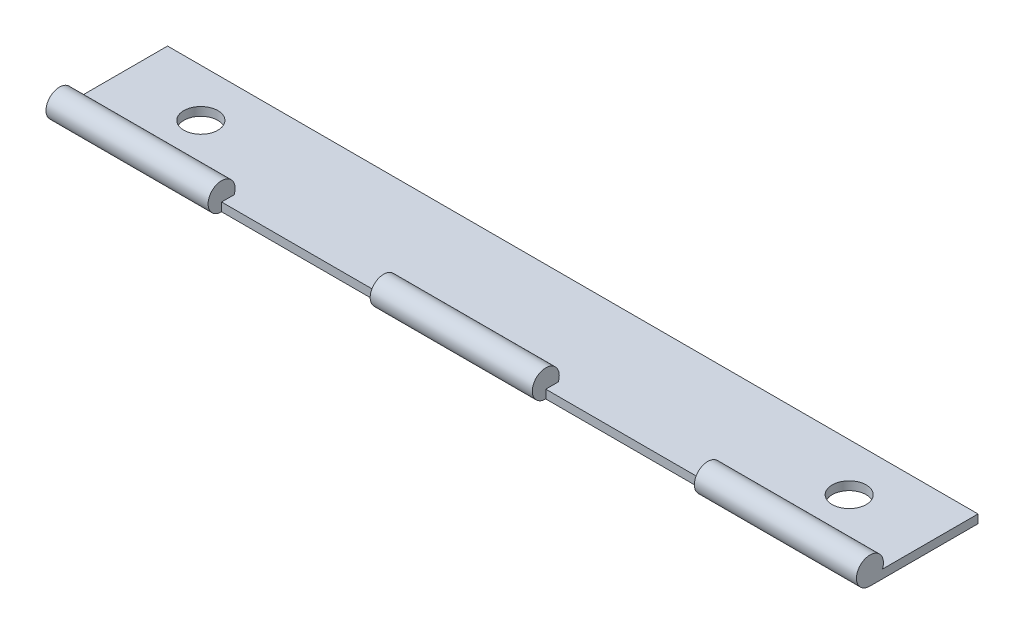
SolidWorks part; units mm, degrees
ref_plane "Front Plane" through (0, 0, 0) normal (0, 0, 1) x (1, 0, 0)
ref_plane "Top Plane" through (0, 0, 0) normal (0, 1, 0) x (1, 0, 0)
ref_plane "Right Plane" through (0, 0, 0) normal (1, 0, 0) x (0, 0, -1)
sketch "Sketch1" plane through (0, 0, 0) normal (0, 1, 0) x (1, 0, 0)
  line L0 (19.05, 12.7) -> (19.05, 0) construction
  line L1 (0, 0) -> (38.1, 0)
  line L2 (0, 0) -> (0, 12.7)
  line L3 (0, 12.7) -> (38.1, 12.7)
  line L4 (38.1, 0) -> (38.1, 12.7)
  dimension "D1" = 12.7
  dimension "D2" = 38.1
extrude "Boss-Extrude1" add sketch "Sketch1" along normal blind 1
sketch "Sketch2" plane through (0, 0, 0) normal (-1, 0, 0) x (0, 0, 1)
  line L0 (0, 0) -> (0, 1.5875) construction
  line L1 (0, 1) -> (0, 0) construction
  circle A0 centre (0, 1.5875) radius 1.5875
  dimension "D1" = 1.5875
extrude "Boss-Extrude2" add sketch "Sketch2" against normal blind 19.05
pattern_linear "MatrizL1" count 2 spacing 38.1 along (1, 0, 0) of "Boss-Extrude1", "Boss-Extrude2"
sketch "Croquis1" plane through (76.2, 0, 0) normal (1, 0, 0) x (0, 0, -1)
  line L1 (12.7, 0) -> (0, 0)
  line L2 (12.7, 0) -> (12.7, 1)
  line L3 (12.7, 1) -> (1.4748, 1)
  line L5 (12.7, 0) -> (0, 1) construction
  line L6 (12.7, 1) -> (0, 0) construction
  arc A0 (1.4748, 1) -> (0, 0) centre (0, 1.5875) ccw
  point P4 (6.35, 0.5)
extrude "Saliente-Extruir1" add sketch "Croquis1" along normal blind 19.05
sketch "Croquis2" plane through (0, 1, 0) normal (0, 1, 0) x (1, 0, 0)
  line L0 (47.625, 1.4748) -> (47.625, 12.7) construction
  line L1 (38.1, 1.4748) -> (57.15, 1.4748) construction
  line L2 (95.25, 12.7) -> (0, 12.7) construction
  line L3 (95.25, 12.7) -> (95.25, 1.4748) construction
  circle A0 centre (85.725, 7.0874) radius 2
  circle A1 centre (9.525, 7.0874) radius 2
  point P12 (95.25, 7.0874)
  dimension "D1" = 9.525
  dimension "D2" = 4
extrude "Cortar-Extruir1" cut sketch "Croquis2" against normal blind 19.05
